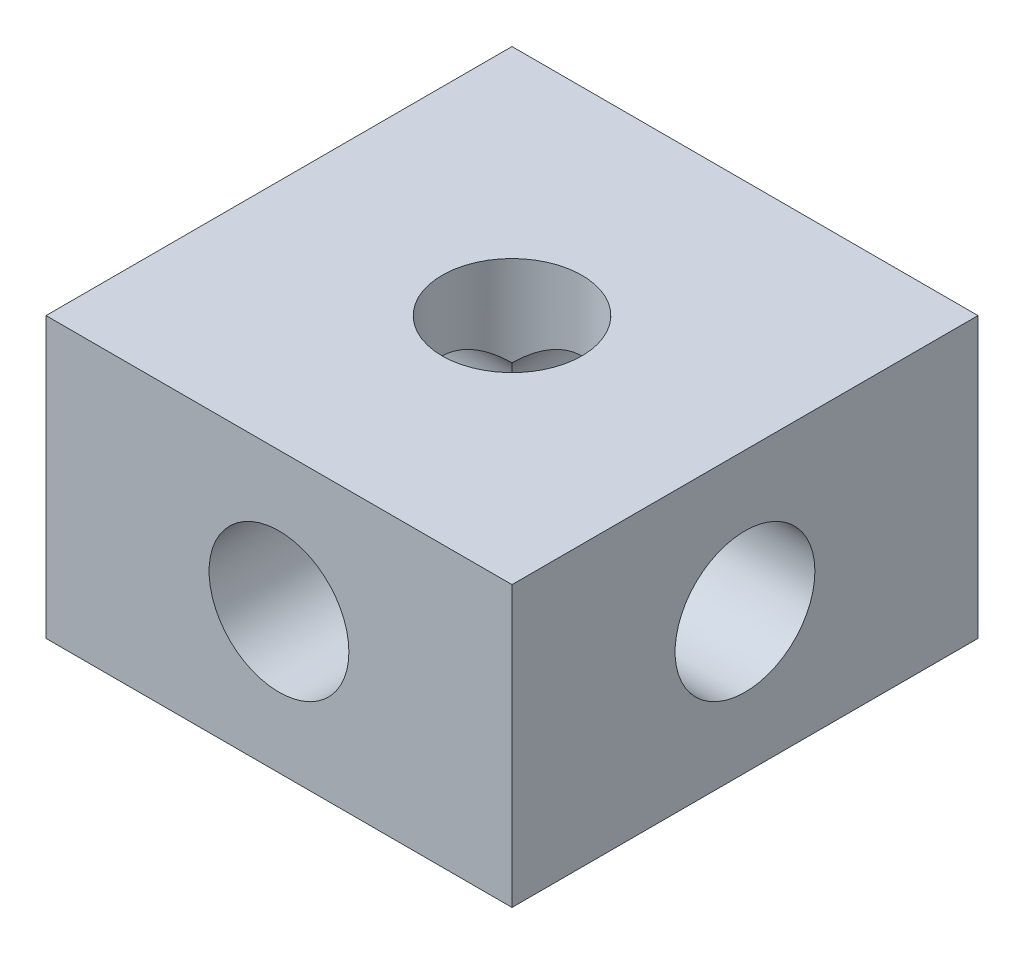
SolidWorks part; units mm, degrees
ref_plane "前视基准面" through (0, 0, 0) normal (0, 0, 1) x (1, 0, 0)
ref_plane "上视基准面" through (0, 0, 0) normal (0, 1, 0) x (1, 0, 0)
ref_plane "右视基准面" through (0, 0, 0) normal (1, 0, 0) x (0, 0, -1)
sketch "草图1" plane through (0, 0, 0) normal (0, 1, 0) x (1, 0, 0)
  line L1 (-5, 5) -> (5, 5)
  line L2 (-5, 5) -> (-5, -5)
  line L3 (-5, -5) -> (5, -5)
  line L4 (5, 5) -> (5, -5)
  line L5 (-5, 5) -> (5, -5) construction
  line L6 (-5, -5) -> (5, 5) construction
  circle A0 centre (0, 0) radius 1.5
  point P0 (0, 0)
  dimension "D2" = 3
  dimension "D1" = 10
extrude "凸台-拉伸1" add sketch "草图1" along normal mid plane 6
sketch "草图3" plane through (0, 0, 5) normal (0, 0, 1) x (1, 0, 0)
  circle A0 centre (0, 0) radius 1.5
  dimension "D1" = 3
extrude "切除-拉伸1" cut sketch "草图3" against normal blind 11
sketch "草图4" plane through (5, 0, 0) normal (1, 0, 0) x (0, 0, -1)
  circle A0 centre (0, 0) radius 1.5
  dimension "D1" = 3
extrude "切除-拉伸2" cut sketch "草图4" against normal blind 11 contours A0
